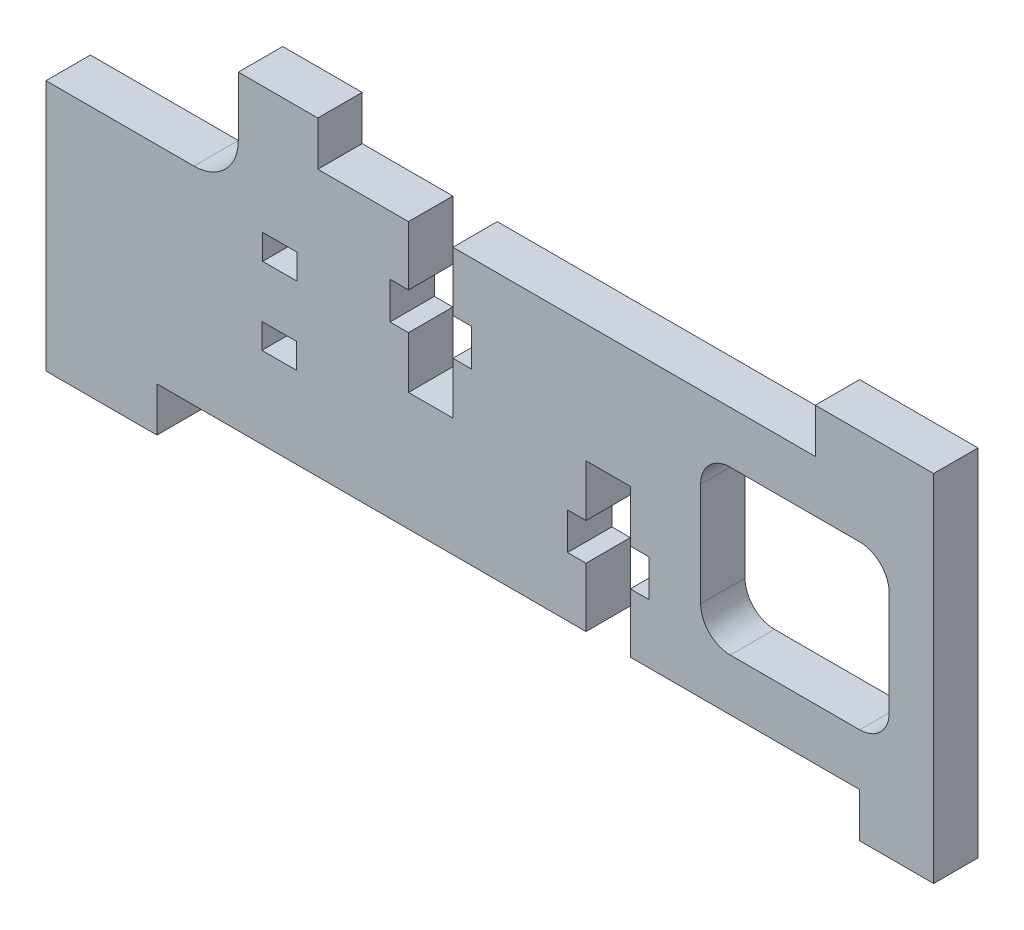
SolidWorks part; units mm, degrees
ref_plane "前视基准面" through (0, 0, 0) normal (0, 0, 1) x (1, 0, 0)
ref_plane "上视基准面" through (0, 0, 0) normal (0, 1, 0) x (1, 0, 0)
ref_plane "右视基准面" through (0, 0, 0) normal (1, 0, 0) x (0, 0, -1)
ref_plane "基准面4" through (0, 0, 3) normal (0, 0, 1) x (1, 0, 0)
sketch "草图1" plane through (0, 0, 3) normal (0, 0, 1) x (1, 0, 0)
  line L0 (23.2531, 5.5836) -> (24.503, 5.5836)
  line L1 (24.503, 5.5836) -> (24.503, 9.5836)
  line L2 (24.503, 9.5836) -> (18.3721, 9.5836)
  line L3 (18.3721, 9.5836) -> (18.3721, 12.5836)
  line L4 (18.3721, 12.5836) -> (12.9991, 12.5836)
  line L5 (12.9991, 12.5836) -> (12.9991, 8.5826)
  line L6 (9.9991, 5.5826) -> (0, 5.5826)
  line L7 (0, 5.5826) -> (0, -11.4164)
  line L8 (0, -11.4164) -> (7.4994, -11.4164)
  line L9 (7.4994, -11.4164) -> (7.4994, -8.4164)
  line L10 (7.4994, -8.4164) -> (36.5002, -8.4164)
  line L11 (36.5002, -8.4164) -> (36.5002, -4.4164)
  line L12 (36.5002, -4.4164) -> (35.2489, -4.4164)
  line L13 (35.2489, -4.4164) -> (35.2489, -1.9164)
  line L14 (35.2489, -1.9164) -> (36.5002, -1.9164)
  line L15 (36.5002, -1.9164) -> (36.5002, 1.5836)
  line L16 (36.5002, 1.5836) -> (39.5003, 1.5836)
  line L17 (39.5003, 1.5836) -> (39.5003, -1.9164)
  line L18 (39.5003, -1.9164) -> (40.7501, -1.9164)
  line L19 (40.7501, -1.9164) -> (40.7501, -4.4164)
  line L20 (40.7501, -4.4164) -> (39.5003, -4.4164)
  line L21 (39.5003, -4.4164) -> (39.5003, -8.4164)
  line L22 (39.5003, -8.4164) -> (54.9988, -8.4164)
  line L23 (54.9988, -8.4164) -> (54.9988, -11.4164)
  line L24 (54.9988, -11.4164) -> (59.9998, -11.4164)
  line L25 (59.9998, -11.4164) -> (59.9998, 12.5836)
  line L26 (59.9998, 12.5836) -> (51.9988, 12.5836)
  line L27 (51.9988, 12.5836) -> (51.9988, 9.5836)
  line L28 (51.9988, 9.5836) -> (27.5031, 9.5836)
  line L29 (27.5031, 9.5836) -> (27.5031, 5.5836)
  line L30 (27.5031, 5.5836) -> (28.7543, 5.5836)
  line L31 (28.7543, 5.5836) -> (28.7543, 3.0836)
  line L32 (28.7543, 3.0836) -> (27.5031, 3.0836)
  line L33 (27.5031, 3.0836) -> (27.5031, -0.4164)
  line L34 (27.5031, -0.4164) -> (24.503, -0.4164)
  line L35 (24.503, -0.4164) -> (24.503, 3.0836)
  line L36 (24.503, 3.0836) -> (23.2531, 3.0836)
  line L37 (23.2531, 3.0836) -> (23.2531, 5.5836)
  line L38 (46.2504, 6.0826) -> (54.9998, 6.0826)
  line L39 (56.9998, 4.0826) -> (56.9998, -2.9164)
  line L40 (54.9998, -4.9164) -> (46.2504, -4.9164)
  line L41 (44.2504, -2.9164) -> (44.2504, 4.0826)
  line L42 (14.6472, 4.0246) -> (16.9748, 4.0246)
  line L43 (16.9748, 4.0246) -> (16.9748, 2.3306)
  line L44 (16.9748, 2.3306) -> (14.6472, 2.3306)
  line L45 (14.6472, 2.3306) -> (14.6472, 4.0246)
  line L46 (14.5948, -1.2134) -> (16.9224, -1.2134)
  line L47 (16.9224, -1.2134) -> (16.9224, -2.9074)
  line L48 (16.9224, -2.9074) -> (14.5948, -2.9074)
  line L49 (14.5948, -2.9074) -> (14.5948, -1.2134)
  arc A0 (12.9991, 8.5826) -> (9.9991, 5.5826) centre (9.9991, 8.5826) cw
  arc A1 (54.9998, 6.0826) -> (56.9998, 4.0826) centre (54.9998, 4.0826) cw
  arc A2 (56.9998, -2.9164) -> (54.9998, -4.9164) centre (54.9998, -2.9164) cw
  arc A3 (46.2504, -4.9164) -> (44.2504, -2.9164) centre (46.2504, -2.9164) cw
  arc A4 (44.2504, 4.0826) -> (46.2504, 6.0826) centre (46.2504, 4.0826) cw
extrude "凸台-拉伸1" add sketch "草图1" against normal blind 3
